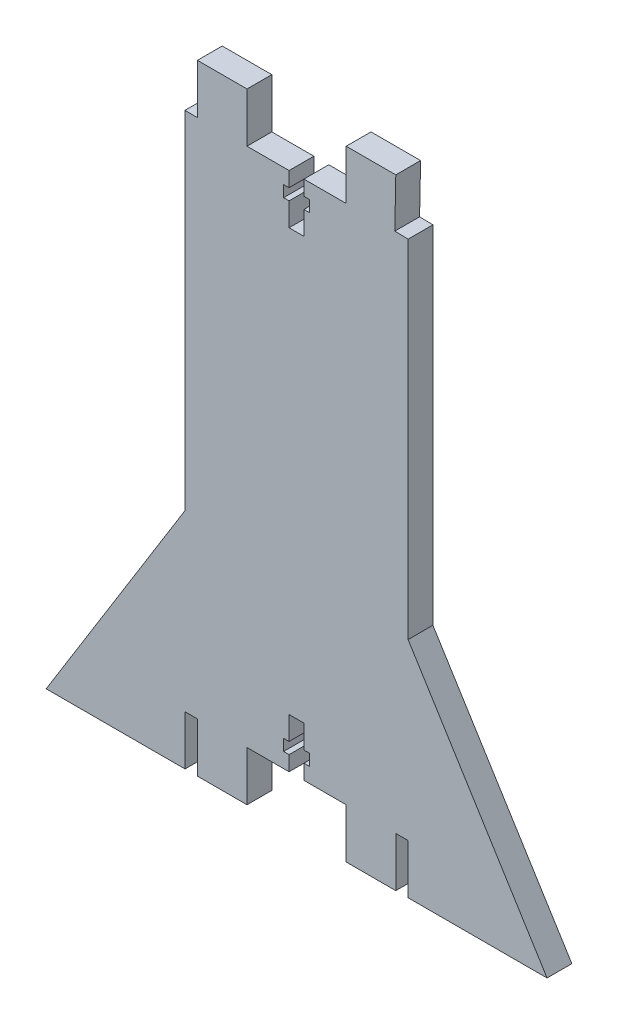
SolidWorks part; units mm, degrees
ref_plane "Front Plane" through (0, 0, 0) normal (0, 0, 1) x (1, 0, 0)
ref_plane "Top Plane" through (0, 0, 0) normal (0, 1, 0) x (1, 0, 0)
ref_plane "Right Plane" through (0, 0, 0) normal (1, 0, 0) x (0, 0, -1)
sketch "Sketch1" plane through (0, 0, 0) normal (0, 0, 1) x (1, 0, 0)
  line L1 (-32.5, -51.1915) -> (-30, -51.1915)
  line L2 (-30, -51.1915) -> (-30, -61.1915)
  line L3 (-30, -61.1915) -> (-20, -61.1915)
  line L4 (-20, -61.1915) -> (-20, -51.1915)
  line L6 (0, -51.1915) -> (0, -61.1915)
  line L7 (0, -61.1915) -> (10, -61.1915)
  line L8 (10, -61.1915) -> (10, -51.1915)
  line L9 (10, -51.1915) -> (12.5, -51.1915)
  line L13 (-11.5189, -51.1915) -> (-8.5189, -51.1915) construction
  line L14 (-8.5189, -51.1915) -> (-8.5189, -48.1915)
  line L15 (-8.5189, -45.8915) -> (-7.4189, -45.8915)
  line L16 (-12.6189, -48.1915) -> (-12.6189, -45.8915)
  line L17 (-7.4189, -48.1915) -> (-8.5189, -48.1915)
  line L18 (-8.5189, -45.8915) -> (-8.5189, -41.1915)
  line L19 (-8.5189, -41.1915) -> (-11.5189, -41.1915)
  line L20 (-11.5189, -41.1915) -> (-11.5189, -45.8915)
  line L21 (-11.5189, -48.1915) -> (-12.6189, -48.1915)
  line L22 (-7.4189, -45.8915) -> (-7.4189, -48.1915)
  line L23 (-12.6189, -45.8915) -> (-11.5189, -45.8915)
  line L24 (-11.5189, -48.1915) -> (-11.5189, -51.1915)
  line L25 (-10.0189, -41.1915) -> (-10.0189, -51.1915) construction
  line L26 (-11.5189, -51.1915) -> (-20, -51.1915)
  line L27 (-8.5189, -51.1915) -> (0, -51.1915)
  line L28 (-10.0189, 43.8085) -> (-10.0189, 53.8085) construction
  line L29 (-11.5189, 53.8085) -> (-8.5189, 53.8085) construction
  line L30 (-10.0189, -57.0002) -> (-10.0189, 91.0448) construction
  line L31 (-8.5189, 53.8085) -> (0, 53.8085)
  line L32 (-11.5189, 53.8085) -> (-20, 53.8085)
  line L33 (-11.5189, 50.8085) -> (-11.5189, 53.8085)
  line L34 (-12.6189, 48.5085) -> (-11.5189, 48.5085)
  line L35 (-7.4189, 48.5085) -> (-7.4189, 50.8085)
  line L36 (-11.5189, 50.8085) -> (-12.6189, 50.8085)
  line L37 (-11.5189, 43.8085) -> (-11.5189, 48.5085)
  line L38 (-8.5189, 43.8085) -> (-11.5189, 43.8085)
  line L39 (-8.5189, 48.5085) -> (-8.5189, 43.8085)
  line L40 (-7.4189, 50.8085) -> (-8.5189, 50.8085)
  line L41 (-12.6189, 50.8085) -> (-12.6189, 48.5085)
  line L42 (-8.5189, 48.5085) -> (-7.4189, 48.5085)
  line L43 (-8.5189, 53.8085) -> (-8.5189, 50.8085)
  line L44 (9.7989, 53.8771) -> (12.4811, 53.8228)
  line L45 (10, 63.8085) -> (9.7989, 53.8771)
  line L46 (0, 63.8085) -> (10, 63.8085)
  line L47 (0, 53.8085) -> (0, 63.8085)
  line L48 (-20, 63.8085) -> (-20, 53.8085)
  line L49 (-30, 63.8085) -> (-20, 63.8085)
  line L50 (-30, 53.8085) -> (-30, 63.8085)
  line L51 (-32.5189, 53.8085) -> (-30, 53.8085)
  line L52 (-32.5, -51.1915) -> (-32.5, -61.1915)
  line L53 (-32.5, -61.1915) -> (-60.5, -61.1915)
  line L54 (-60.5, -61.1915) -> (-32.5189, -16.1038)
  line L55 (-32.5189, 53.8085) -> (-32.5189, -16.1038)
  line L56 (12.5, -51.1915) -> (12.5, -61.1915)
  line L57 (12.5, -61.1915) -> (40.5, -61.1915)
  line L58 (40.5, -61.1915) -> (12.4811, -16.1038)
  line L59 (12.4811, -16.1038) -> (12.4811, 53.8228)
  point P2 (0, -56.1915)
  point P57 (-10.0189, 43.8085)
  dimension "D1" = 10
  dimension "D2" = 10
  dimension "D3" = 10
  dimension "D4" = 20
  dimension "D5" = 28
  dimension "D6" = 2.5
  dimension "D7" = 5.2
  dimension "D8" = 3
  dimension "D9" = 2.3
  dimension "D10" = 3
  dimension "D11" = 10
  dimension "D12" = 10
  dimension "D13" = 28
  dimension "D14" = 2.5
  dimension "D15" = 3
  dimension "D16" = 3
  dimension "D17" = 5.2
  dimension "D18" = 45
  dimension "D19" = 10
  dimension "D20" = 20
  dimension "D21" = 22.5
extrude "Boss-Extrude1" add sketch "Sketch1" along normal blind 5
